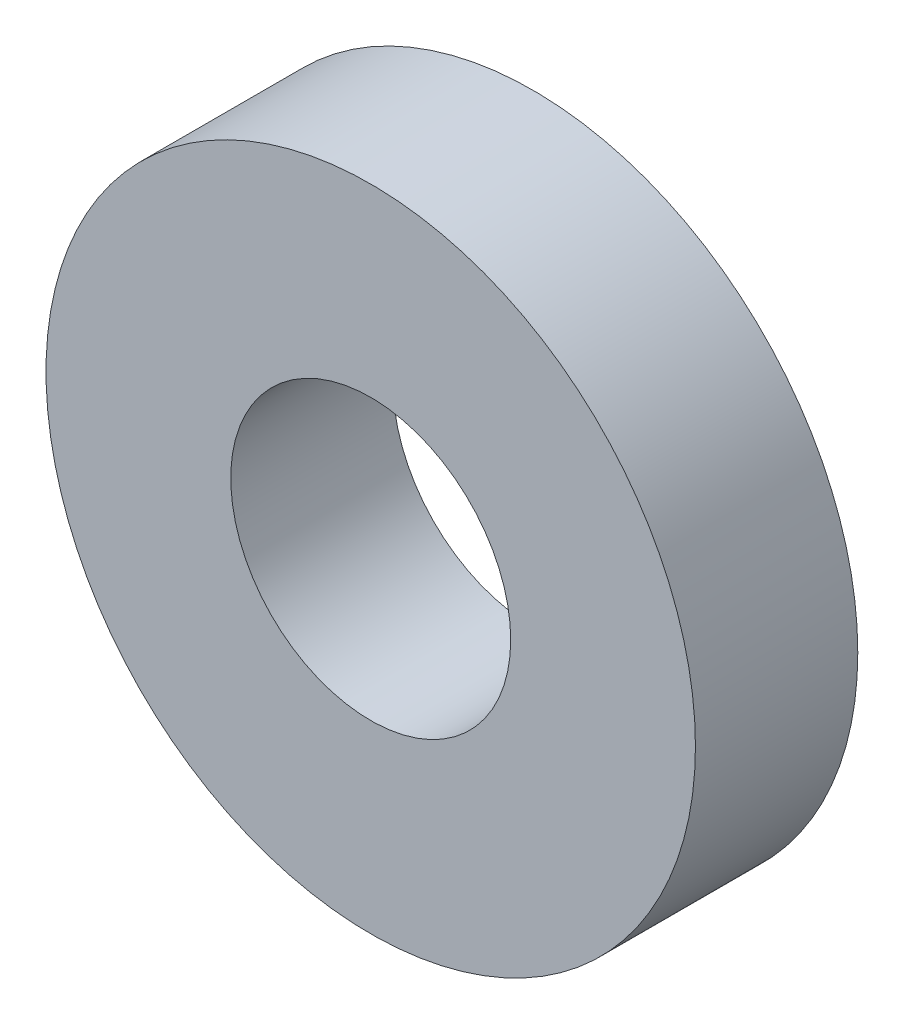
SolidWorks part; units mm, degrees
material "Brass"
ref_plane "Front Plane" through (0, 0, 0) normal (0, 0, 1) x (1, 0, 0)
ref_plane "Top Plane" through (0, 0, 0) normal (0, 1, 0) x (1, 0, 0)
ref_plane "Right Plane" through (0, 0, 0) normal (1, 0, 0) x (0, 0, -1)
sketch "Sketch1" plane through (0, 0, 0) normal (0, 0, 1) x (1, 0, 0)
  circle A0 centre (0, 0) radius 2.7375
  circle A1 centre (0, 0) radius 6.35
  dimension "D1" = 5.475
  dimension "D2" = 12.7
extrude "Boss-Extrude1" add sketch "Sketch1" along normal blind 3.175
equation "\"D1@Sketch1\"= 5.47500000mm"
